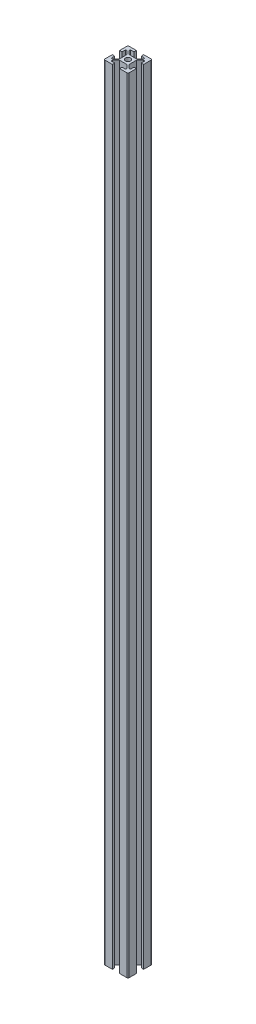
SolidWorks part; units mm, degrees
ref_plane "Front Plane" through (0, 0, 0) normal (0, 0, 1) x (1, 0, 0)
ref_plane "Top Plane" through (0, 0, 0) normal (0, 1, 0) x (1, 0, 0)
ref_plane "Right Plane" through (0, 0, 0) normal (1, 0, 0) x (0, 0, -1)
sketch "Sketch1" plane through (0, 0, 0) normal (0, 1, 0) x (1, 0, 0)
  line L5 (-3, 10) -> (-10, 10)
  line L6 (-4, 3) -> (-7, 6)
  line L7 (-4, -4) -> (4, -4)
  line L8 (-4, -4) -> (-4, 4)
  line L9 (-4, 4) -> (4, 4)
  line L10 (4, -4) -> (4, 4)
  line L11 (-8, 6) -> (-7, 6)
  line L12 (-8, 6) -> (-8, 3)
  line L16 (-3, 8) -> (-3, 10)
  line L21 (-8, 3) -> (-10, 3)
  line L22 (-6, 8) -> (-6, 7)
  line L23 (-10, 3) -> (-10, 10)
  line L24 (-3, 4) -> (-6, 7)
  line L25 (3, 10) -> (10, 10)
  line L26 (6, 8) -> (3, 8)
  line L27 (-6, 8) -> (-3, 8)
  line L28 (3, 8) -> (3, 10)
  line L29 (-10, 10) -> (-4, 4)
  line L30 (6, 8) -> (6, 7)
  line L31 (3, 4) -> (6, 7)
  line L32 (4, 3) -> (7, 6)
  line L33 (8, 6) -> (7, 6)
  line L34 (8, 6) -> (8, 3)
  line L35 (8, 3) -> (10, 3)
  line L36 (10, 3) -> (10, 10)
  line L37 (10, -3) -> (10, -10)
  line L38 (8, -6) -> (8, -3)
  line L39 (8, -3) -> (10, -3)
  line L40 (8, -6) -> (7, -6)
  line L41 (4, -3) -> (7, -6)
  line L42 (3, -4) -> (6, -7)
  line L43 (6, -8) -> (6, -7)
  line L44 (6, -8) -> (3, -8)
  line L45 (3, -8) -> (3, -10)
  line L46 (3, -10) -> (10, -10)
  line L47 (-3, -10) -> (-10, -10)
  line L48 (-6, -8) -> (-3, -8)
  line L49 (-3, -8) -> (-3, -10)
  line L50 (-6, -8) -> (-6, -7)
  line L51 (-3, -4) -> (-6, -7)
  line L52 (-4, -3) -> (-7, -6)
  line L53 (-8, -6) -> (-7, -6)
  line L54 (-8, -6) -> (-8, -3)
  line L55 (-8, -3) -> (-10, -3)
  line L56 (-10, -3) -> (-10, -10)
  circle A0 centre (0, 0) radius 2.1
  point P0 (0, 0)
  point P55 (0, 0)
  dimension "D3" = 3
  dimension "D1" = 4.2
  dimension "D2" = 4
  dimension "D4" = 4
  dimension "D5" = 6
  dimension "D7" = 8
  dimension "D8" = 10
  dimension "D6" = 4
extrude "Boss-Extrude1" add sketch "Sketch1" along normal blind 650 contours L29 L23 L21 L12 L11 L6 L8 | L5 L29 L9 L24 L22 L27 L16 | L35 L36 L25 L28 L26 L30 L31 L9 L10 L32 L33 L34 | L7 L10 L9 L8 A0 | L45 L46 L37 L39 L38 L40 L41 L10 L7 L42 L43 L44 | L55 L56 L47 L49 L48 L50 L51 L7 L8 L52 L53 L54
fillet "Fillet1" radius 1 4 edges at (-10, 325, 10) (-10, 325, -10) (10, 325, -10) (10, 325, 10)
ref_plane "Plane1" through (0, 325, 0) normal (0, 1, 0) x (1, 0, 0)
